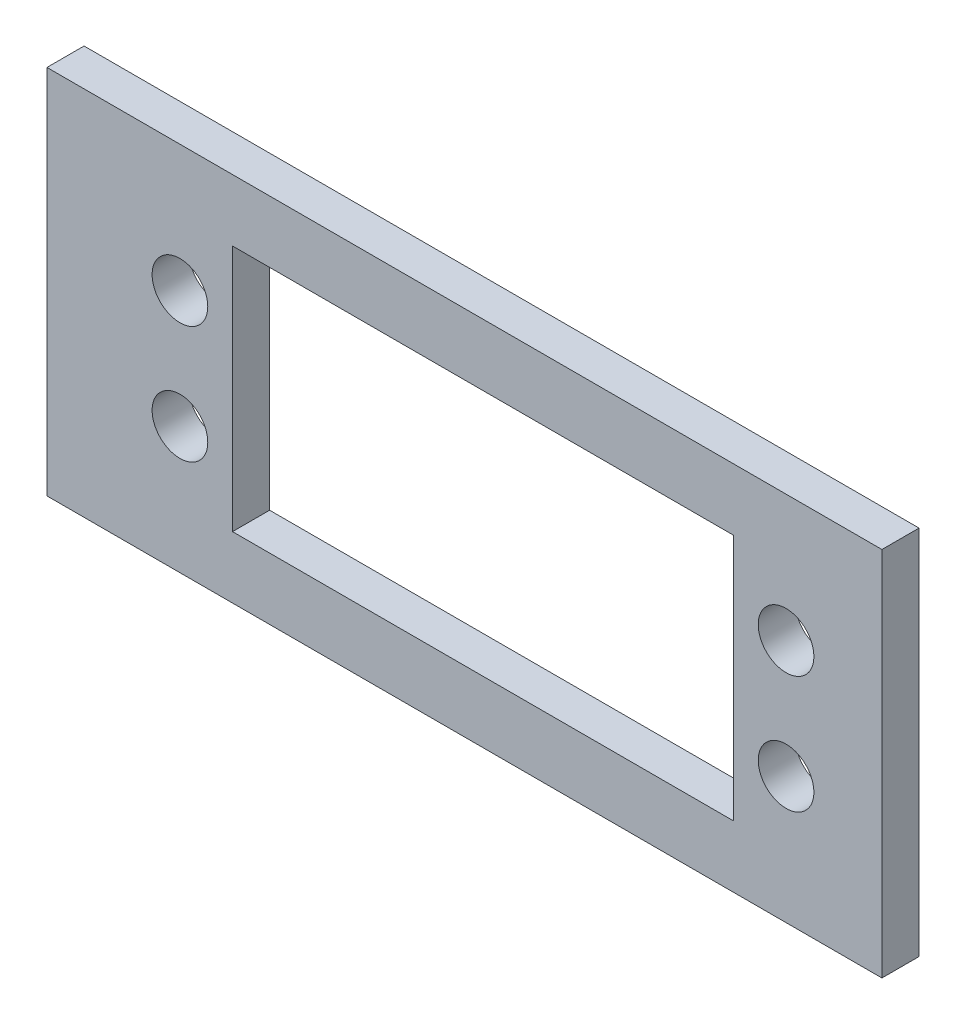
SolidWorks part; units mm, degrees
material "Acrylic (Medium-high impact)"
ref_plane "Front Plane" through (0, 0, 0) normal (0, 0, 1) x (1, 0, 0)
ref_plane "Top Plane" through (0, 0, 0) normal (0, 1, 0) x (1, 0, 0)
ref_plane "Right Plane" through (0, 0, 0) normal (1, 0, 0) x (0, 0, -1)
sketch "Sketch1" plane through (0, 0, 0) normal (0, 0, 1) x (1, 0, 0)
  line L0 (3, 39.1045) -> (3, -10.4424) construction
  line L1 (0, 0) -> (67.5, 0)
  line L2 (0, 0) -> (0, 30)
  line L3 (0, 30) -> (67.5, 30)
  line L4 (67.5, 0) -> (67.5, 30)
  line L5 (8, 39.1045) -> (8, -11.8341) construction
  line L6 (15, 40.0787) -> (15, -10.9991) construction
  line L7 (10.75, 37.2072) -> (10.75, -15.0478) construction
  line L8 (67.5, 40.0787) -> (67.5, -8.2156) construction
  line L9 (59.75, 39.1045) -> (59.75, -10.3032) construction
  line L10 (55.5, 39.1045) -> (55.5, -7.6588) construction
  line L11 (-18.494, 15) -> (89.8367, 15) construction
  line L12 (84.9486, 25) -> (-12.0205, 25) construction
  line L13 (-10.6994, 5) -> (105.0294, 5) construction
  line L14 (83.8917, 10.25) -> (-6.604, 10.25) construction
  line L15 (-6.604, 19.75) -> (82.1743, 19.75) construction
  line L17 (15, 5) -> (55.5, 5)
  line L18 (15, 5) -> (15, 25)
  line L19 (15, 25) -> (55.5, 25)
  line L20 (55.5, 5) -> (55.5, 25)
  circle A0 centre (10.75, 19.75) radius 2.25
  circle A1 centre (10.75, 10.25) radius 2.25
  circle A2 centre (59.75, 19.75) radius 2.25
  circle A3 centre (59.75, 10.25) radius 2.25
  dimension "D13" = 4.5
  dimension "D14" = 4.5
  dimension "D15" = 4.5
  dimension "D16" = 4.5
  dimension "D1" = 3
  dimension "D2" = 5
  dimension "D3" = 7
  dimension "D4" = 4.25
  dimension "D5" = 0
  dimension "D6" = 12
  dimension "D7" = 4.25
  dimension "D8" = 15
  dimension "D9" = 4.75
  dimension "D10" = 4.75
  dimension "D11" = 10
  dimension "D12" = 10
  dimension "D17" = 9.5
  dimension "D18" = 40.5
  dimension "D19" = 30
extrude "Boss-Extrude1" add sketch "Sketch1" along normal blind 3
